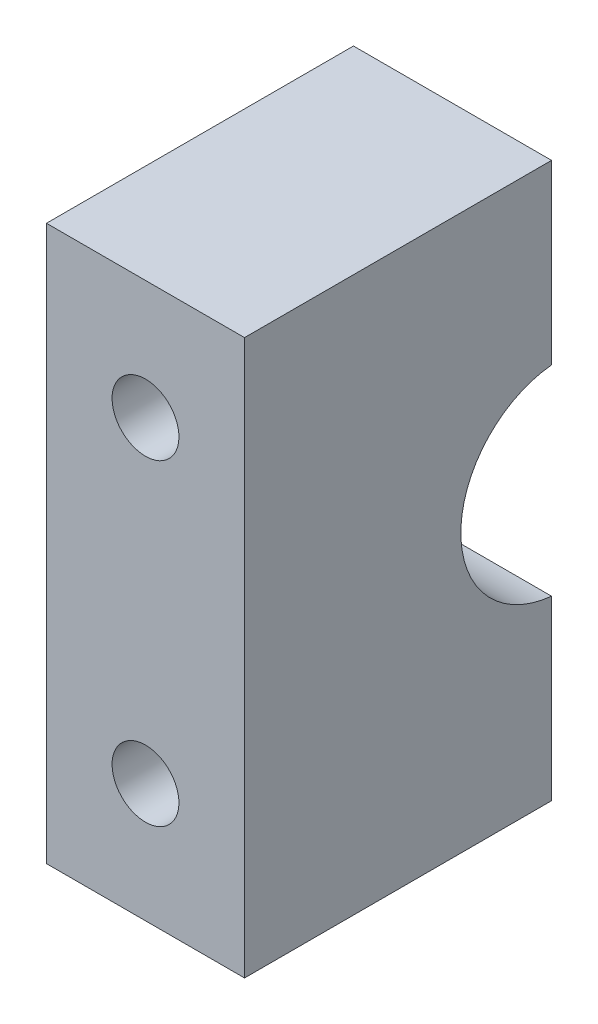
SolidWorks part; units mm, degrees
ref_plane "front" through (0, 0, 0) normal (0, 0, 1) x (1, 0, 0)
ref_plane "top" through (0, 0, 0) normal (0, 1, 0) x (1, 0, 0)
ref_plane "right" through (0, 0, 0) normal (1, 0, 0) x (0, 0, -1)
sketch "Sketch1" plane through (0, 0, 0) normal (1, 0, 0) x (0, 0, -1)
  line L0 (-50.8, 44.45) -> (-50.8, -44.45)
  line L1 (-1.5875, -16.0507) -> (-1.5875, -44.45)
  line L3 (-50.8, -44.45) -> (-1.5875, -44.45)
  line L4 (-1.5875, 44.45) -> (-50.8, 44.45)
  line L6 (-1.5875, 44.45) -> (-1.5875, 16.0507)
  arc A0 (-1.5875, 16.0507) -> (-1.5875, -16.0507) centre (0, 0) ccw
  point P2 (-50.8, 0)
  dimension "D4" = 49.2125
  dimension "D1" = 16.129
  dimension "D2" = 88.9
  dimension "D3" = 50.8
extrude "Base-Extrude" add sketch "Sketch1" along normal mid plane 31.75
sketch "Sketch3" plane through (0, 0, 1.5875) normal (0, 0, -1) x (-1, 0, 0)
  point P0 (0, 25.4)
  point P1 (0, -25.4)
  dimension "D1" = 25.4
  dimension "D2" = 25.4
hole_wizard "1/2-13 Tapped Hole2" positions "3DSketch3" profile "Sketch6" tap size "1/2-13" standard "Ansi Inch" end condition through all
sketch3d "3DSketch3"
  point P0 (0, 25.4, 1.5875)
  point P1 (0, -25.4, 1.5875)
sketch "Sketch6" plane through (0, 25.4, 1.5875) normal (1, 0, 0) x (0, 1, 0)
  line L0 (0, 0) -> (0, 49.2125)
  line L1 (0, 49.2125) -> (5.3581, 49.2125)
  line L3 (5.3581, 49.2125) -> (5.3581, 25.4)
  line L4 (6.35, 25.4) -> (5.3581, 25.4)
  line L5 (6.35, 25.4) -> (6.35, 0.7937)
  line L6 (6.35, 0.7937) -> (7.1438, 0)
  line L7 (7.1438, 0) -> (0, 0)
  line L8 (-6.35, 0.7937) -> (-7.1438, 0) construction
  line L11 (0, -6.35) -> (0, 107.95) construction
  dimension "Thru Tap Drill Dia." = 10.7163
  dimension "Thru Tap Drill Depth" = 49.2125
  dimension "Thread Dia." = 12.7
  dimension "Thread Depth" = 25.4
  dimension "Near C'Sink Dia." = 14.2875
  dimension "Near C'Sink Angle" = 90
chamfer "Chamfer1" [suppressed] distance 0.762 angle 45
